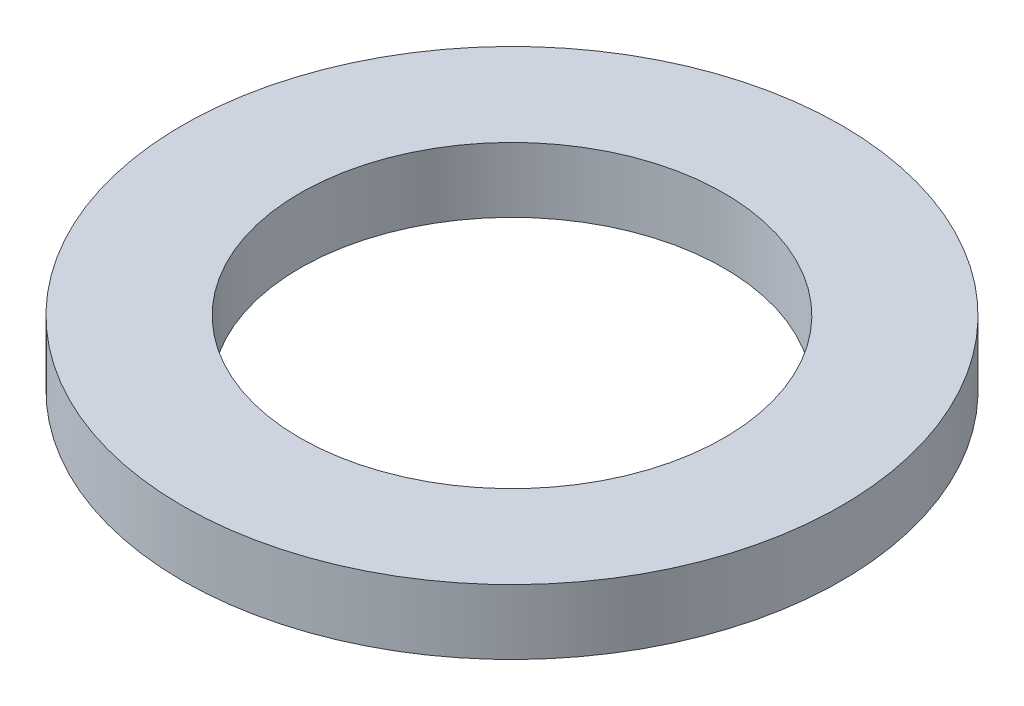
SolidWorks part; units mm, degrees
material "Beech"
ref_plane "Front Plane" through (0, 0, 0) normal (0, 0, 1) x (1, 0, 0)
ref_plane "Top Plane" through (0, 0, 0) normal (0, 1, 0) x (1, 0, 0)
ref_plane "Right Plane" through (0, 0, 0) normal (1, 0, 0) x (0, 0, -1)
sketch "Sketch1" plane through (0, 0, 0) normal (0, 1, 0) x (1, 0, 0)
  circle A0 centre (0, 0) radius 20.75
  circle A1 centre (0, 0) radius 32.25
  dimension "D1" = 41.5
  dimension "D2" = 64.5
extrude "Boss-Extrude1" add sketch "Sketch1" along normal blind 6.35
